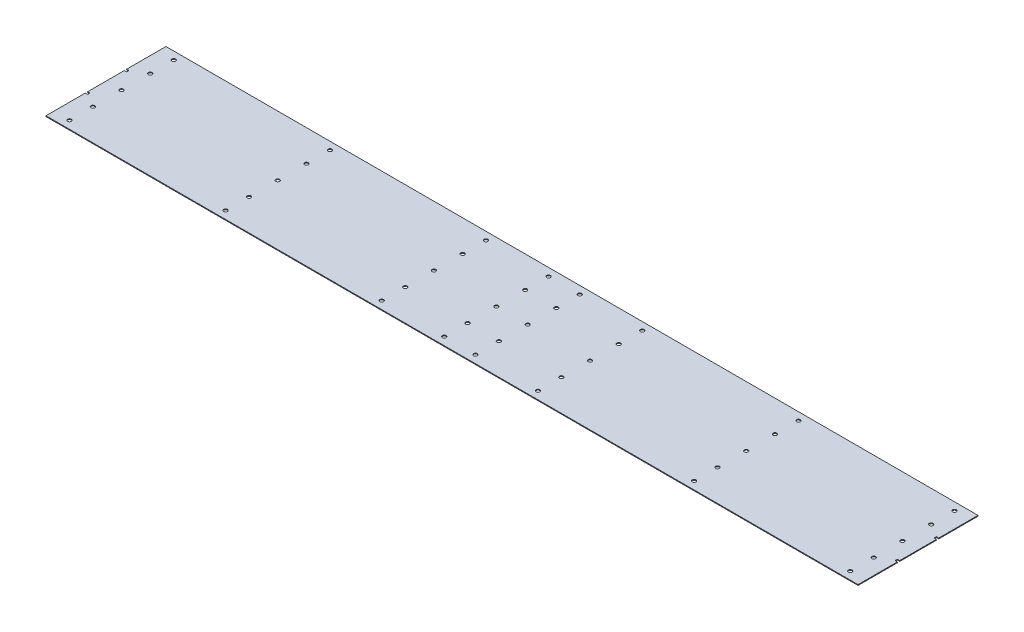
SolidWorks part; units mm, degrees
ref_plane "Front Plane" through (0, 0, 0) normal (0, 0, 1) x (1, 0, 0)
ref_plane "Top Plane" through (0, 0, 0) normal (0, 1, 0) x (1, 0, 0)
ref_plane "Right Plane" through (0, 0, 0) normal (1, 0, 0) x (0, 0, -1)
sketch "Sketch1" plane through (0, 0, 0) normal (0, 1, 0) x (1, 0, 0)
  line L0 (-20, -26.5) -> (-20, -76.8)
  line L1 (-20, -76.8) -> (1020, -76.8)
  line L2 (1020, -76.8) -> (1020, -26.5)
  line L3 (1020, -26.5) -> (-20, -26.5) construction
  line L4 (0, 0) -> (-17, 0) construction
  line L5 (-20, -26.5) -> (-17, -26.5)
  line L7 (-17, 26.5) -> (-20, 26.5)
  line L8 (-20, 26.5) -> (-20, 76.8)
  line L9 (-20, 76.8) -> (1020, 76.8)
  line L10 (1020, 76.8) -> (1020, 26.5)
  line L11 (1020, 26.5) -> (1017, 26.5)
  line L13 (1017, -26.5) -> (1020, -26.5)
  line L14 (0, 36.8) -> (480, 36.8) construction
  line L15 (-17, 26.5) -> (-17, 23.5)
  line L16 (-17, 26.5) -> (1017, 26.5) construction
  line L17 (1017, 26.5) -> (1017, -26.5) construction
  line L18 (-17, 26.5) -> (-17, -26.5) construction
  line L19 (-17, 23.5) -> (-20, 23.5)
  line L20 (-20, 23.5) -> (-20, -23.5)
  line L21 (-20, -23.5) -> (-17, -23.5)
  line L22 (-17, -23.5) -> (-17, -26.5)
  line L23 (1017, 26.5) -> (1017, 23.5)
  line L24 (1017, 23.5) -> (1020, 23.5)
  line L25 (1020, 23.5) -> (1020, -23.5)
  line L26 (1020, -23.5) -> (1017, -23.5)
  line L27 (1017, -23.5) -> (1017, -26.5)
  line L28 (1020, 0) -> (1017, 0) construction
  line L29 (480, 36.8) -> (480, -36.8) construction
  line L30 (-17, 0) -> (-20, 0) construction
  line L31 (0, 36.8) -> (0, -36.8) construction
  line L32 (480, -36.8) -> (0, -36.8) construction
  line L33 (0, 36.8) -> (0, 66.8) construction
  line L34 (0, 66.8) -> (480, 66.8) construction
  line L35 (480, 66.8) -> (480, 36.8) construction
  line L36 (480, -36.8) -> (480, -66.8) construction
  line L37 (480, -66.8) -> (0, -66.8) construction
  line L38 (0, -66.8) -> (0, -36.8) construction
  line L39 (0, 0) -> (480, 0) construction
  line L40 (200, 66.8) -> (200, 36.8) construction
  line L41 (200, 36.8) -> (200, 0) construction
  line L42 (200, 0) -> (200, -36.8) construction
  line L43 (200, -36.8) -> (200, -66.8) construction
  line L44 (500, 76.8) -> (500, -76.8) construction
  line L45 (480, 66.8) -> (500, 66.8) construction
  line L46 (500, 66.8) -> (520, 66.8) construction
  line L47 (520, 66.8) -> (520, -66.8) construction
  line L48 (520, -66.8) -> (480, -66.8) construction
  line L49 (480, -36.8) -> (520, -36.8) construction
  line L50 (400, 66.8) -> (400, -66.8) construction
  line L51 (480, 0) -> (520, 0) construction
  line L53 (480, 36.8) -> (520, 36.8) construction
  line L54 (600, 66.8) -> (600, -66.8) construction
  line L56 (800, 66.8) -> (800, -66.8) construction
  line L58 (1000, 66.8) -> (1000, -66.8) construction
  circle A0 centre (0, -36.8) radius 2.4
  circle A30 centre (0, 36.8) radius 2.4
  circle A31 centre (0, -66.8) radius 2.4
  circle A32 centre (0, 66.8) radius 2.4
  circle A33 centre (200, -66.8) radius 2.4
  circle A34 centre (200, -36.8) radius 2.4
  circle A35 centre (200, 36.8) radius 2.4
  circle A36 centre (200, 66.8) radius 2.4
  circle A53 centre (0, 0) radius 2.4
  circle A54 centre (480, 0) radius 2.4
  circle A55 centre (200, 0) radius 2.4
  circle A59 centre (480, 66.8) radius 2.4
  circle A60 centre (480, 36.8) radius 2.4
  circle A61 centre (480, -36.8) radius 2.4
  circle A62 centre (480, -66.8) radius 2.4
  circle A63 centre (400, -66.8) radius 2.4
  circle A64 centre (400, -36.8) radius 2.4
  circle A65 centre (400, 36.8) radius 2.4
  circle A66 centre (400, 66.8) radius 2.4
  circle A67 centre (600, -66.8) radius 2.4
  circle A68 centre (600, -36.8) radius 2.4
  circle A69 centre (600, 36.8) radius 2.4
  circle A70 centre (600, 66.8) radius 2.4
  circle A71 centre (800, -66.8) radius 2.4
  circle A72 centre (800, -36.8) radius 2.4
  circle A73 centre (800, 36.8) radius 2.4
  circle A74 centre (800, 66.8) radius 2.4
  circle A75 centre (1000, -66.8) radius 2.4
  circle A76 centre (1000, -36.8) radius 2.4
  circle A77 centre (1000, 36.8) radius 2.4
  circle A78 centre (1000, 66.8) radius 2.4
  circle A79 centre (520, -66.8) radius 2.4
  circle A80 centre (520, -36.8) radius 2.4
  circle A81 centre (520, 0) radius 2.4
  circle A82 centre (520, 36.8) radius 2.4
  circle A83 centre (520, 66.8) radius 2.4
  circle A84 centre (600, 0) radius 2.4
  circle A85 centre (800, 0) radius 2.4
  circle A86 centre (1000, 0) radius 2.4
  circle A87 centre (400, 0) radius 2.4
  point P2 (-18.5, 23.5)
  point P17 (0, 51.8)
  dimension "D12" = 4.8
  dimension "D8" = 3
  dimension "D1" = 3
  dimension "D6" = 30
  dimension "D7" = 10
  dimension "D4" = 20
  dimension "D15" = 200
  dimension "D3" = 13.3
  dimension "D11" = 13.3
  dimension "D2" = 47
  dimension "D5" = 20
  dimension "D10" = 40
  dimension "D13" = 1040
  dimension "D9" = 6
  dimension "D14" = 2
extrude "Boss-Extrude1" add sketch "Sketch1" along normal blind 1 contours L27 L26 L25 L24 L23 L11 L10 L9 L8 L7 L15 L19 L20 L21 L22 L5 L0 L1 L2 L13 A54 A53 A36 A35 A34 A33 A32 A31 A30 A0
equation "\"skin_sheetmetal_thickness\"= 0.80"
equation "\"base_width_skin_spacer\" = \"base_width_skin_target_width\" - 4 * \"skin_sheetmetal_thickness\" - 2 * \"base_width_skin_target_bend_radius\""
equation "\"base_width_skin_inner\" = \"base_width_skin_spacer\" + 2 * \"skin_sheetmetal_thickness\""
equation "\"base_width_skin_outer\" = \"base_width_skin_inner\" + 2 * \"skin_sheetmetal_thickness\""
equation "\"bend_cut_width\"= 3"
equation "\"bend_cut_length\"= 3"
equation "\"bend_offset_inner\"= 12.5"
equation "\"bend_offset_outer\" = \"bend_offset_inner\" + \"skin_sheetmetal_thickness\""
equation "\"border_offset_ends\"= 20"
equation "\"border_offset_sides\"= 10"
equation "\"border_offset_flange_horiz\"= 10"
equation "\"rivet_size\"= 4.8"
equation "\"rivet_offset_ends\"= \"rivet_spacing_horiz\"/2 - \"border_offset_ends\""
equation "\"rivet_spacing_horiz\"= 200"
equation "\"rivet_spacing_vert\"= 30"
equation "\"rivet_spacing_offset_right\"= 40"
equation "\"base_length\"= 200"
equation "\"base_width_skin_spacer_length\" = 1560"
equation "\"bend_offset_spacer_tab\"= 21.0"
equation "\"D6@Sketch1\"=\"rivet_spacing_vert\""
equation "\"D3@Sketch1\"=\"bend_offset_outer\""
equation "\"D1@Sketch1\"=\"bend_cut_length\""
equation "\"D8@Sketch1\"=\"bend_cut_width\""
equation "\"D2@Sketch1\"=\"base_width_skin_outer\""
equation "\"D4@Sketch1\"=\"border_offset_ends\""
equation "\"D7@Sketch1\"=\"border_offset_flange_horiz\""
equation "\"D12@Sketch1\"=\"rivet_size\""
equation "\"D15@Sketch1\"=\"rivet_spacing_horiz\""
equation "\"D5@Sketch1\"=\"border_offset_ends\""
equation "\"D10@Sketch1\"=\"rivet_spacing_offset_right\""
equation "\"base_width_skin_target_width\" = 50"
equation "\"base_width_skin_target_bend_radius\" = 1.5"
